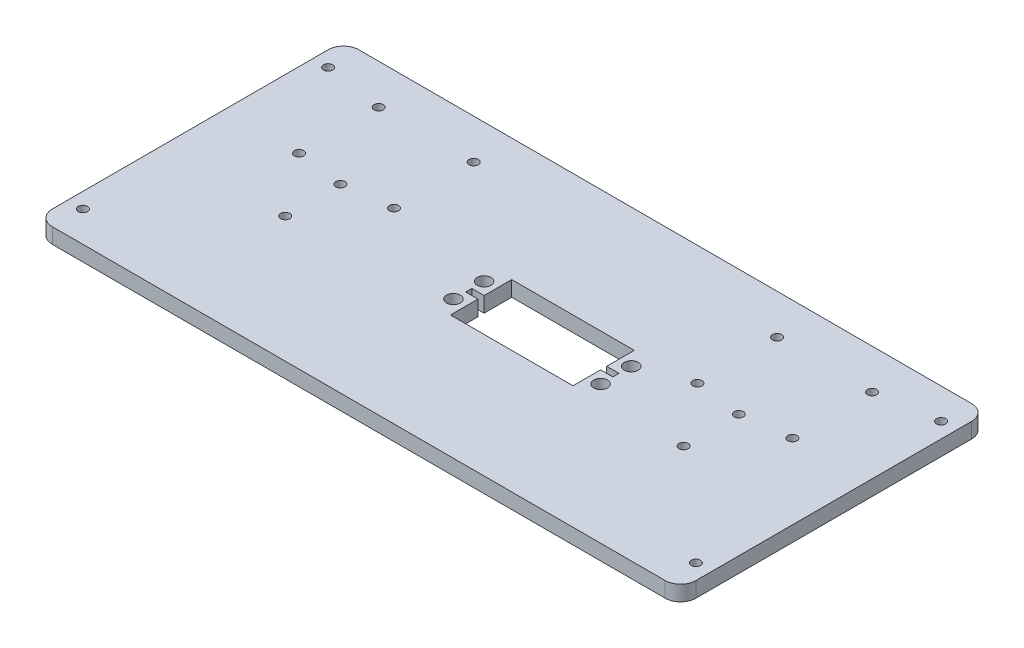
SolidWorks part; units mm, degrees
ref_plane "前视基准面" through (0, 0, 0) normal (0, 0, 1) x (1, 0, 0)
ref_plane "上视基准面" through (0, 0, 0) normal (0, 1, 0) x (1, 0, 0)
ref_plane "右视基准面" through (0, 0, 0) normal (1, 0, 0) x (0, 0, -1)
other "Configuration Table"
sketch "草图1" plane through (0, 0, 0) normal (0, 1, 0) x (1, 0, 0)
  line L1 (-210, 100) -> (0, 100)
  line L2 (-210, 100) -> (-210, 0)
  line L3 (-210, 0) -> (0, 0)
  line L4 (0, 100) -> (0, 0)
  dimension "D1" = 210
  dimension "D2" = 100
extrude "凸台-拉伸1" add sketch "草图1" along normal blind 5
fillet "圆角1" radius 5 4 edges at (0, 2.5, -100) (-210, 2.5, -100) (-210, 2.5, 0) (0, 2.5, 0)
sketch "草图2" plane through (0, 5, 0) normal (0, 1, 0) x (1, 0, 0)
  line L0 (-5, 100) -> (-205, 100) construction
  line L1 (-210, 95) -> (-210, 5) construction
  line L2 (-105, 100) -> (-105, 0) construction
  line L3 (-205, 0) -> (-5, 0) construction
  line L4 (-210, 50) -> (0, 50) construction
  line L5 (0, 5) -> (0, 95) construction
  circle A0 centre (-205, 90) radius 1.5
  circle A1 centre (-205, 10) radius 1.5
  circle A2 centre (-5, 10) radius 1.5
  circle A3 centre (-5, 90) radius 1.5
  dimension "D1" = 3
  dimension "D2" = 10
  dimension "D3" = 5
extrude "切除-拉伸1" cut sketch "草图2" against normal up to surface (5 mm away) up to face at (-105, 0, -50)
sketch "草图4" plane through (0, 0, 0) normal (0, -1, 0) x (1, 0, 0)
  line L0 (-5, -100) -> (-205, -100) construction
  line L1 (-115.1, -60) -> (-75.1, -60)
  line L2 (-115.1, -60) -> (-115.1, -51)
  line L3 (-115.1, -40) -> (-75.1, -40)
  line L4 (-75.1, -60) -> (-75.1, -51)
  line L5 (-210, -95) -> (-210, -5) construction
  line L6 (-205, 0) -> (-5, 0) construction
  line L7 (0, -5) -> (0, -95) construction
  line L8 (-119.1, -50) -> (-71.1, -50) construction
  line L9 (-95.1, -40) -> (-95.1, -60) construction
  line L10 (-115.1, -49) -> (-119.1, -49)
  line L11 (-115.1, -51) -> (-119.1, -51)
  line L12 (-119.1, -49) -> (-119.1, -51)
  line L13 (-75.1, -51) -> (-71.1, -51)
  line L14 (-71.1, -49) -> (-71.1, -51)
  line L15 (-75.1, -49) -> (-71.1, -49)
  line L16 (-115.1, -49) -> (-115.1, -40)
  line L17 (-75.1, -49) -> (-75.1, -40)
  circle A0 centre (-119.1, -45) radius 2.25
  circle A1 centre (-119.1, -55) radius 2.25
  circle A2 centre (-71.1, -55) radius 2.25
  circle A3 centre (-71.1, -45) radius 2.25
  point P32 (-119.1, -49.848)
  point P33 (-71.1, -49.5683)
  dimension "D6" = 4.5
  dimension "D1" = 40
  dimension "D2" = 94.9
  dimension "D3" = 40
  dimension "D4" = 75.1
  dimension "D5" = 4
  dimension "D7" = 10
  dimension "D8" = 2
  dimension "D9" = 4
  dimension "D10" = 10
extrude "切除-拉伸2" cut sketch "草图4" against normal up to surface (5 mm away) up to face at (-5, 5, -91.5)
sketch "草图6" plane through (0, 0, 0) normal (0, -1, 0) x (1, 0, 0)
  line L0 (-40, -41) -> (-40, -59) construction
  line L1 (-5, -100) -> (-205, -100) construction
  line L2 (0, -5) -> (0, -95) construction
  line L3 (-105, 0) -> (-105, -100) construction
  line L4 (-205, 0) -> (-5, 0) construction
  line L6 (-170, -41) -> (-170, -59) construction
  circle A0 centre (-40, -41) radius 1.5
  circle A1 centre (-40, -59) radius 1.5
  circle A2 centre (-170, -59) radius 1.5
  circle A3 centre (-170, -41) radius 1.5
  circle A4 centre (-185.5, -87) radius 1.5
  circle A5 centre (-185.5, -61) radius 1.5
  circle A6 centre (-154.5, -87) radius 1.5
  circle A7 centre (-154.5, -61) radius 1.5
  circle A8 centre (-55.5, -87) radius 1.5
  circle A9 centre (-24.5, -87) radius 1.5
  circle A10 centre (-55.5, -61) radius 1.5
  circle A11 centre (-24.5, -61) radius 1.5
  point P4 (-40, -50)
  dimension "D2" = 3
  dimension "D3" = 3
  dimension "D6" = 3
  dimension "D7" = 3
  dimension "D1" = 18
  dimension "D4" = 50
  dimension "D5" = 40
  dimension "D8" = 26
  dimension "D9" = 13
  dimension "D10" = 31
extrude "切除-拉伸3" cut sketch "草图6" against normal up to surface (5 mm away) up to face at (-71.1, 5, -42.75)
